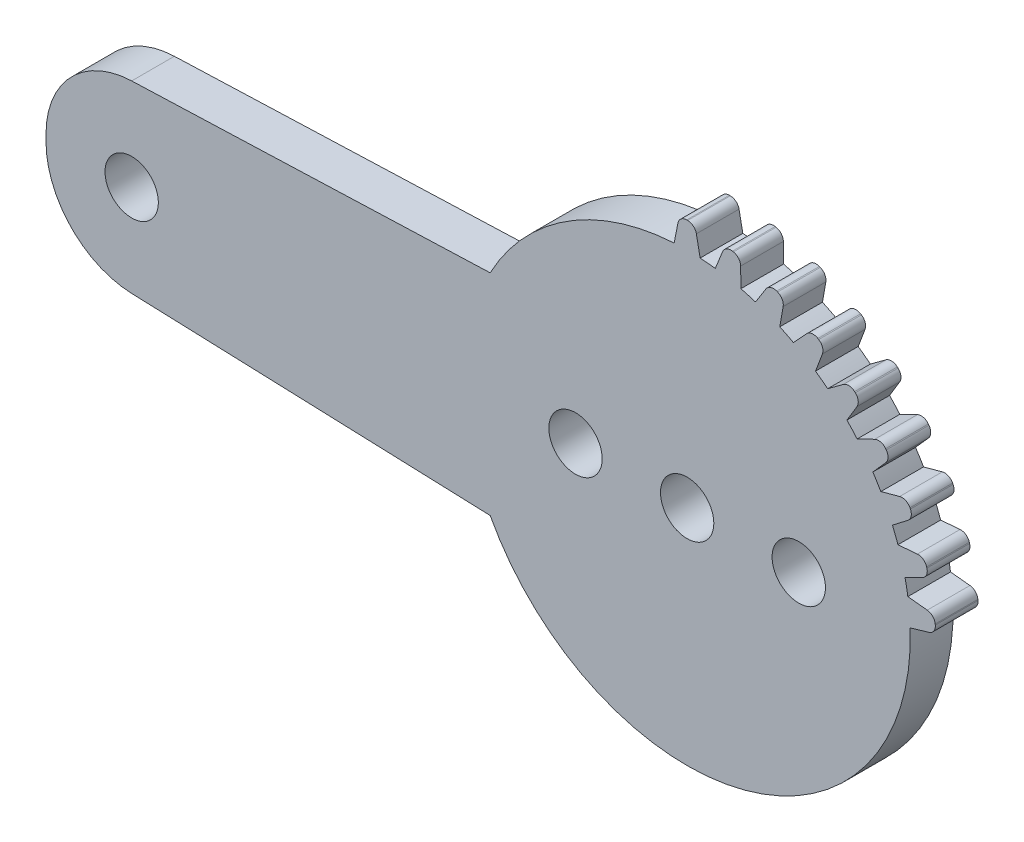
SolidWorks part; units mm, degrees
ref_plane "Front Plane" through (0, 0, 0) normal (0, 0, 1) x (1, 0, 0)
ref_plane "Top Plane" through (0, 0, 0) normal (0, 1, 0) x (1, 0, 0)
ref_plane "Right Plane" through (0, 0, 0) normal (1, 0, 0) x (0, 0, -1)
sketch "Sketch1" plane through (0, 0, 0) normal (0, 0, 1) x (1, 0, 0)
  line L2 (55, 0) -> (-55, 0) construction
  line L21 (2.5471, 13.778) -> (2.6021, 13.7677)
  line L24 (5.0354, 13.0753) -> (5.0876, 13.0551)
  line L25 (-11.0756, 5.91) -> (-31.2358, 5.1755)
  line L26 (-11.0756, -5.91) -> (-31.2358, -5.1755)
  line L27 (-36.0538, -0.1788) -> (-36.0538, 0.1788)
  line L28 (7.3523, 11.9275) -> (7.3998, 11.898)
  line L29 (9.4188, 10.3734) -> (9.4601, 10.3357)
  line L30 (11.1645, 8.4661) -> (11.1982, 8.4214)
  line L31 (12.53, 6.2704) -> (12.555, 6.2204)
  line L32 (13.4689, 3.8613) -> (13.4842, 3.8075)
  line L33 (13.9491, 1.3206) -> (13.9542, 1.265)
  line L138 (1.5839, 12.4534) -> (1.9909, 13.472)
  line L139 (-0.7314, 12.5324) -> (-0.5184, 13.6085)
  line L140 (0.7314, 12.5324) -> (0.5184, 13.6085)
  line L141 (-0.028, 14.0114) -> (0.028, 14.0114)
  line L142 (3.0218, 12.1847) -> (3.0102, 13.2815)
  line L143 (3.8452, 11.9504) -> (4.4325, 12.8768)
  line L144 (5.2092, 11.4219) -> (5.3994, 12.5022)
  line L145 (5.9756, 11.0403) -> (6.7231, 11.8431)
  line L146 (7.2193, 10.2703) -> (7.6047, 11.2972)
  line L147 (7.9026, 9.7543) -> (8.7848, 10.4061)
  line L148 (8.9835, 8.7689) -> (9.5511, 9.7075)
  line L149 (9.5603, 8.1361) -> (10.5474, 8.6147)
  line L150 (10.4419, 6.9688) -> (11.1722, 7.7872)
  line L151 (10.8926, 6.2409) -> (11.9507, 6.5299)
  line L152 (11.5446, 4.9315) -> (12.4129, 5.6017)
  line L153 (11.8539, 4.1331) -> (12.9471, 4.2228)
  line L154 (12.2542, 2.7262) -> (13.2309, 3.2255)
  line L155 (12.4115, 1.8846) -> (13.5026, 1.7719)
  line L156 (12.5465, 0.4281) -> (13.5983, 0.7394)
  arc A21 (1.5839, 12.4534) -> (0.7314, 12.5324) centre (0, 0) ccw
  arc A22 (3.8452, 11.9504) -> (3.0218, 12.1847) centre (0, 0) ccw
  arc A23 (5.9756, 11.0403) -> (5.2092, 11.4219) centre (0, 0) ccw
  arc A24 (7.9026, 9.7543) -> (7.2193, 10.2703) centre (0, 0) ccw
  arc A25 (9.5603, 8.1361) -> (8.9835, 8.7689) centre (0, 0) ccw
  arc A26 (10.8926, 6.2409) -> (10.4419, 6.9688) centre (0, 0) ccw
  arc A27 (11.8539, 4.1331) -> (11.5446, 4.9315) centre (0, 0) ccw
  arc A28 (12.4115, 1.8846) -> (12.2542, 2.7262) centre (0, 0) ccw
  circle A29 centre (6.2769, 0) radius 1.5
  circle A30 centre (-6.2769, 0) radius 1.5
  circle A31 centre (0, 0) radius 1.5
  arc A32 (-31.2358, -5.1755) -> (-36.0538, -0.1788) centre (-31.0538, -0.1788) cw
  arc A33 (-31.2358, 5.1755) -> (-36.0538, 0.1788) centre (-31.0538, 0.1788) ccw
  circle A34 centre (-31.2358, 0) radius 1.5
  arc A35 (-11.0756, -5.91) -> (12.5465, 0.4281) centre (0, 0) ccw
  arc A87 (-0.7314, 12.5324) -> (-11.0756, 5.91) centre (0, 0) ccw
  arc A88 (0.5184, 13.6085) -> (0.028, 14.0114) centre (0.028, 13.5114) ccw
  arc A89 (-0.5184, 13.6085) -> (-0.028, 14.0114) centre (-0.028, 13.5114) cw
  arc A90 (1.9909, 13.472) -> (2.5471, 13.778) centre (2.4552, 13.2865) cw
  arc A91 (3.0102, 13.2815) -> (2.6021, 13.7677) centre (2.5102, 13.2762) ccw
  arc A92 (4.4325, 12.8768) -> (5.0354, 13.0753) centre (4.8548, 12.6091) cw
  arc A93 (5.3994, 12.5022) -> (5.0876, 13.0551) centre (4.907, 12.5889) ccw
  arc A94 (6.7231, 11.8431) -> (7.3523, 11.9275) centre (7.0891, 11.5023) cw
  arc A95 (7.6047, 11.2972) -> (7.3998, 11.898) centre (7.1366, 11.4729) ccw
  arc A96 (8.7848, 10.4061) -> (9.4188, 10.3734) centre (9.0819, 10.0039) cw
  arc A97 (9.5511, 9.7075) -> (9.4601, 10.3357) centre (9.1232, 9.9662) ccw
  arc A98 (10.5474, 8.6147) -> (11.1645, 8.4661) centre (10.7655, 8.1648) cw
  arc A99 (11.1722, 7.7872) -> (11.1982, 8.4214) centre (10.7992, 8.1201) ccw
  arc A100 (11.9507, 6.5299) -> (12.53, 6.2704) centre (12.0825, 6.0476) cw
  arc A101 (12.4129, 5.6017) -> (12.555, 6.2204) centre (12.1074, 5.9975) ccw
  arc A102 (12.9471, 4.2228) -> (13.4689, 3.8613) centre (12.988, 3.7245) cw
  arc A103 (13.2309, 3.2255) -> (13.4842, 3.8075) centre (13.0033, 3.6707) ccw
  arc A104 (13.5026, 1.7719) -> (13.9491, 1.3206) centre (13.4512, 1.2745) cw
  arc A105 (13.5983, 0.7394) -> (13.9542, 1.265) centre (13.4563, 1.2188) ccw
  point P8 (0, 0)
  point P9 (0, 0)
  point P18 (-36.0538, -5)
  point P21 (-36.0538, 5)
  point P24 (0, 0)
  point P25 (0, 0)
  dimension "D1" = 6.2769
  dimension "D2" = 6.2769
  dimension "D3" = 0.5
  dimension "D4" = 11.82
  dimension "D5" = 12.5538
  dimension "D8" = 5
  dimension "D6" = 10
extrude "Boss-Extrude1" add sketch "Sketch1" along normal blind 2.4 contours L25 A33 L27 A32 L26 A35 L156 A105 L33 A104 L155 A28 L154 A103 L32 A102 L153 A27 L152 A101 L31 A100 L151 A26 L150 A99 L30 A98 L149 A25 L148 A97 L29 A96 L147 A24 L146 A95 L28 A94 L145 A23 L144 A93 L24 A92 L143 A22 L142 A91 L21 A90 L138 A21 L140 A88 L141 A89 L139 A87
